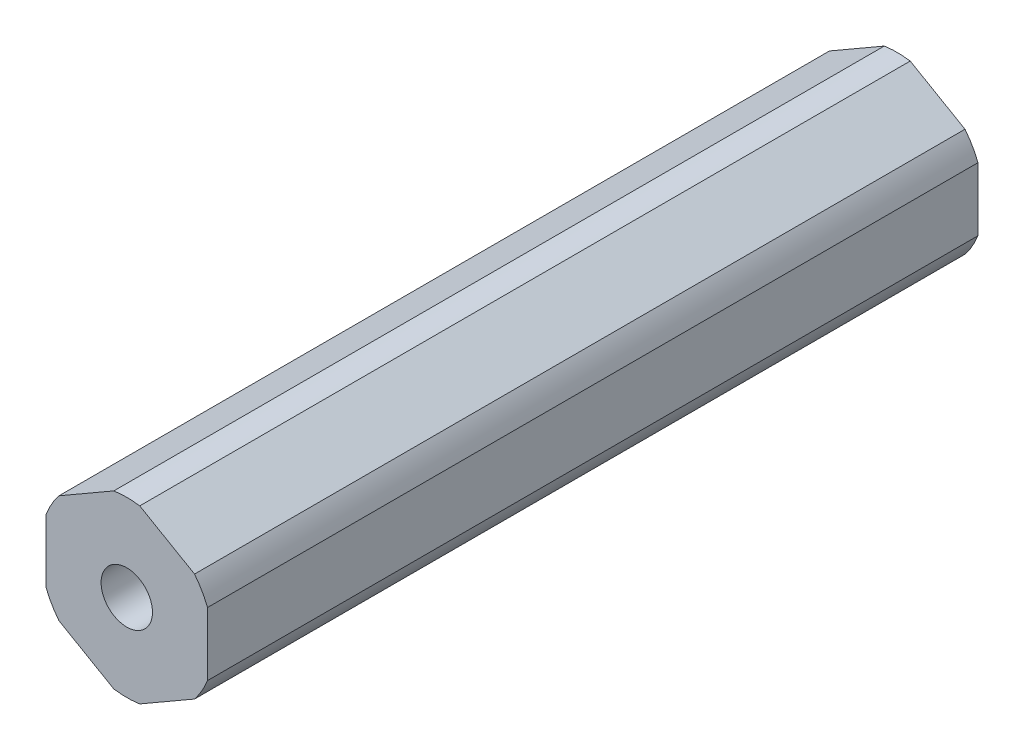
SolidWorks part; units mm, degrees
material "7075-T6 (SN)"
ref_plane "Front Plane" through (0, 0, 0) normal (0, 0, 1) x (1, 0, 0)
ref_plane "Top Plane" through (0, 0, 0) normal (0, 1, 0) x (1, 0, 0)
ref_plane "Right Plane" through (0, 0, 0) normal (1, 0, 0) x (0, 0, -1)
sketch "Sketch1" plane through (0, 0, 0) normal (0, 0, 1) x (1, 0, 0)
  line L1 (6.35, 3.6662) -> (0, 7.3323)
  line L2 (0, 7.3323) -> (-6.35, 3.6662)
  line L3 (-6.35, 3.6662) -> (-6.35, -3.6662)
  line L4 (-6.35, -3.6662) -> (0, -7.3323)
  line L5 (0, -7.3323) -> (6.35, -3.6662)
  line L6 (6.35, -3.6662) -> (6.35, 3.6662)
  circle A0 centre (0, 0) radius 6.35 construction
  circle A1 centre (0, 0) radius 6.8199
  dimension "D1" = 12.7
  dimension "D2" = 13.6398
extrude "Boss-Extrude1" add sketch "Sketch1" along normal mid plane 60.579 contours L6 A1 L1 L2 L3 L4 L5
hole_wizard "#10-32 Tapped Hole1" positions "Sketch2" profile "Sketch3" tap size "#10-32" standard "ANSI Inch"
sketch "Sketch2" plane through (0, 0, 30.2895) normal (0, 0, 1) x (1, 0, 0)
  point P0 (0, 0)
sketch "Sketch3" plane through (0, 0, 30.2895) normal (1, 0, 0) x (0, -1, 0)
  line L0 (0, 0) -> (0, 13.2428)
  line L1 (0, 13.2428) -> (2.0193, 12.0294)
  line L2 (2.0193, 12.0294) -> (2.0193, 0)
  line L5 (2.0193, 0) -> (0, 0)
  line L10 (0, 13.2428) -> (-2.0193, 12.0294) construction
  line L11 (0, -6.35) -> (0, 107.95) construction
  dimension "Tap Drill Dia." = 4.0386
  dimension "Tap Drill Depth" = 12.0294
  dimension "Drill Angle" = 118
cosmetic thread "Hole Thread1" parameters "D1"=9.652, "D2"=4.826
hole_wizard "#10-32 Tapped Hole2" positions "Sketch4" profile "Sketch5" tap size "#10-32" standard "ANSI Inch"
sketch "Sketch4" plane through (0, 0, -30.2895) normal (0, 0, -1) x (-1, 0, 0)
  point P0 (0, 0)
sketch "Sketch5" plane through (0, 0, -30.2895) normal (1, 0, 0) x (0, 1, 0)
  line L0 (0, 0) -> (0, 13.2428)
  line L1 (0, 13.2428) -> (2.0193, 12.0294)
  line L2 (2.0193, 12.0294) -> (2.0193, 0)
  line L5 (2.0193, 0) -> (0, 0)
  line L10 (0, 13.2428) -> (-2.0193, 12.0294) construction
  line L11 (0, -6.35) -> (0, 107.95) construction
  dimension "Tap Drill Dia." = 4.0386
  dimension "Tap Drill Depth" = 12.0294
  dimension "Drill Angle" = 118
cosmetic thread "Hole Thread2" parameters "D1"=9.652, "D2"=4.826
